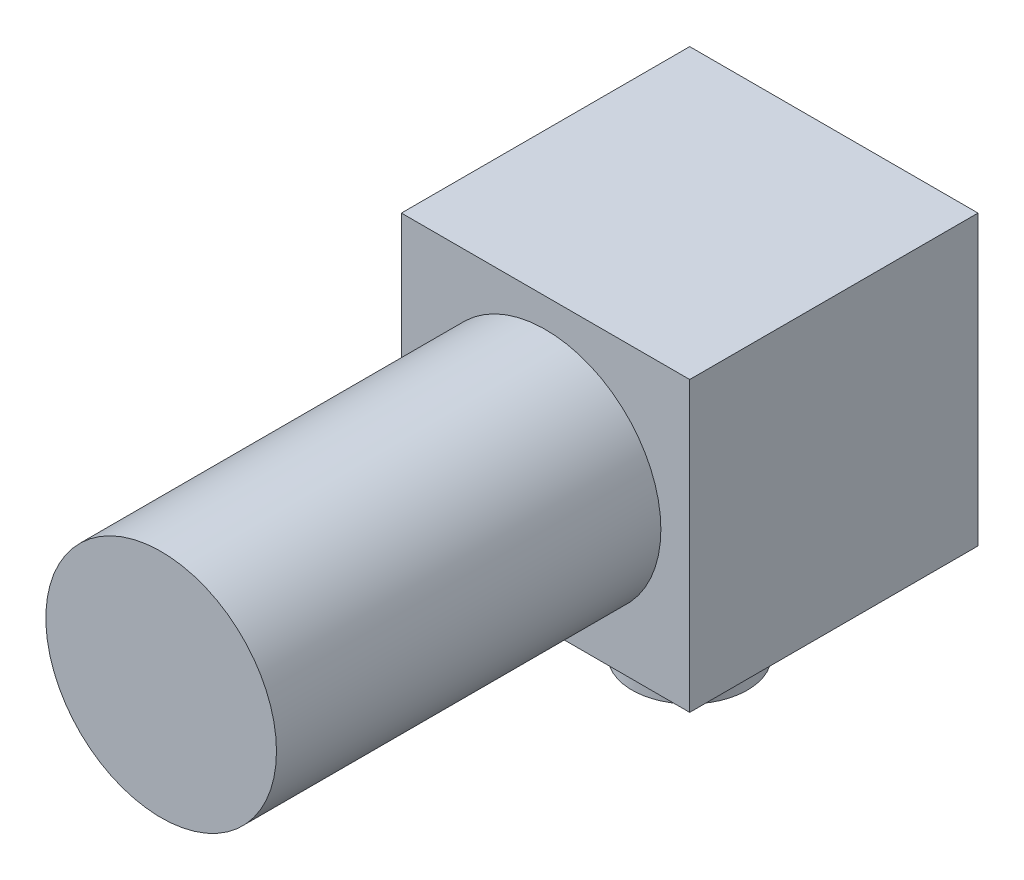
SolidWorks part; units mm, degrees
ref_plane "Front Plane" through (0, 0, 0) normal (0, 0, 1) x (1, 0, 0)
ref_plane "Top Plane" through (0, 0, 0) normal (0, 1, 0) x (1, 0, 0)
ref_plane "Right Plane" through (0, 0, 0) normal (1, 0, 0) x (0, 0, -1)
sketch "Sketch1" plane through (0, 0, 0) normal (0, 0, 1) x (1, 0, 0)
  line L1 (-7.5, 7.5) -> (7.5, 7.5)
  line L2 (-7.5, 7.5) -> (-7.5, -7.5)
  line L3 (-7.5, -7.5) -> (7.5, -7.5)
  line L4 (7.5, 7.5) -> (7.5, -7.5)
  line L5 (-7.5, 7.5) -> (7.5, -7.5) construction
  line L6 (-7.5, -7.5) -> (7.5, 7.5) construction
  point P0 (0, 0)
  dimension "D1" = 15
  dimension "D2" = 15
extrude "Boss-Extrude1" add sketch "Sketch1" along normal blind 15
sketch "Sketch2" plane through (0, 0, 15) normal (0, 0, 1) x (1, 0, 0)
  circle A0 centre (0, 0) radius 6
  dimension "D1" = 12
extrude "Boss-Extrude2" add sketch "Sketch2" along normal blind 20
sketch "Sketch3" plane through (0, 0, 0) normal (0, 0, -1) x (-1, 0, 0)
  circle A0 centre (0, 0) radius 6
  dimension "D1" = 12
extrude "Cut-Extrude1" cut sketch "Sketch3" against normal blind 10
sketch "Sketch4" plane through (0, -7.5, 0) normal (0, -1, 0) x (1, 0, 0)
  line L0 (-7.5, 7.5) -> (7.5, 7.5) construction
  line L1 (-7.5, 15) -> (-7.5, 0) construction
  line L2 (7.5, 15) -> (7.5, 0) construction
  line L3 (0, 15) -> (0, 0) construction
  line L4 (-7.5, 15) -> (7.5, 15) construction
  circle A0 centre (0, 7.5) radius 3
  dimension "D1" = 6
extrude "Boss-Extrude3" add sketch "Sketch4" along normal blind 5
